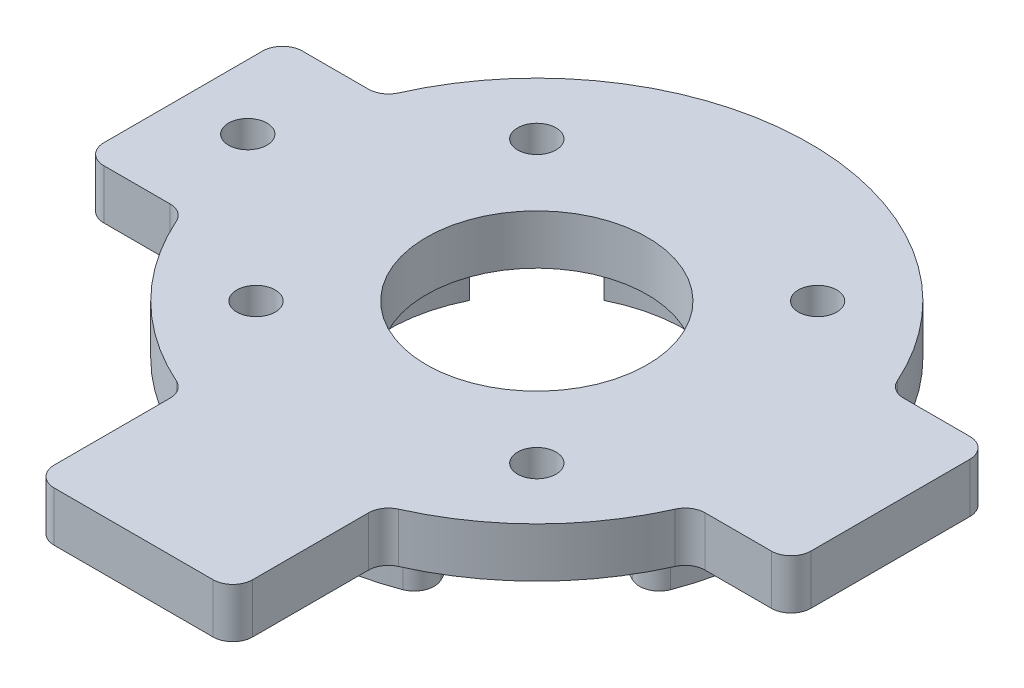
SolidWorks part; units mm, degrees
ref_plane "Front" through (0, 0, 0) normal (0, 0, 1) x (1, 0, 0)
ref_plane "Top" through (0, 0, 0) normal (0, 1, 0) x (1, 0, 0)
ref_plane "Right" through (0, 0, 0) normal (1, 0, 0) x (0, 0, -1)
sketch "Sketch1" plane through (0, 0, 0) normal (0, 1, 0) x (1, 0, 0)
  line L0 (0, -34.925) -> (0, 34.925) construction
  line L1 (-17.9605, 17.9605) -> (17.9605, 17.9605) construction
  line L2 (-17.9605, 17.9605) -> (-17.9605, -17.9605) construction
  line L3 (-17.9605, -17.9605) -> (17.9605, -17.9605) construction
  line L4 (17.9605, 17.9605) -> (17.9605, -17.9605) construction
  line L5 (-17.9605, 17.9605) -> (17.9605, -17.9605) construction
  line L6 (-17.9605, -17.9605) -> (17.9605, 17.9605) construction
  line L7 (-19.05, 50.8) -> (19.05, 50.8) construction
  line L8 (-19.05, 50.8) -> (-19.05, -50.8) construction
  line L9 (-19.05, -50.8) -> (19.05, -50.8) construction
  line L10 (19.05, 50.8) -> (19.05, -50.8) construction
  line L11 (-19.05, 50.8) -> (19.05, -50.8) construction
  line L12 (-19.05, -50.8) -> (19.05, 50.8) construction
  line L13 (12.7, -51.5841) -> (-12.7, -51.5841)
  line L14 (12.7, -51.5841) -> (12.7, -32.5341)
  line L15 (12.7, -32.5341) -> (-12.7, -32.5341)
  line L16 (-12.7, -51.5841) -> (-12.7, -32.5341)
  line L17 (-45.2341, 0) -> (0, 0) construction
  line L18 (-32.5341, 12.7) -> (-45.2341, 12.7)
  line L19 (-32.5341, 12.7) -> (-32.5341, -12.7)
  line L20 (-32.5341, -12.7) -> (-45.2341, -12.7)
  line L21 (-45.2341, 12.7) -> (-45.2341, -12.7)
  line L22 (32.5341, -12.7) -> (45.2341, -12.7)
  line L23 (45.2341, 12.7) -> (45.2341, -12.7)
  line L24 (32.5341, 12.7) -> (45.2341, 12.7)
  circle A0 centre (0, 0) radius 25.4 construction
  circle A1 centre (0, 0) radius 34.925
  circle A2 centre (0, 0) radius 14.1288
  point P0 (0, 0)
  point P18 (0, -32.5341)
  dimension "D1" = 50.8
  dimension "D4" = 69.85
  dimension "D5" = 28.2575
  dimension "D2" = 101.6
  dimension "D3" = 38.1
  dimension "D6" = 19.05
  dimension "D7" = 25.4
  dimension "D8" = 25.4
  dimension "D9" = 12.7
extrude "Stock Extrude" add sketch "Sketch1" along normal blind 6.35 contours A1 L18 L21 L20 | L15 A1 L19 A2 | A1 L22 L23 L24 | L19 A1 | A1 L16 L13 L14 | L15 A1
hole_wizard "#10 (0.1935) Diameter Hole1" positions "Sketch2" profile "Sketch3" hole size "#10" standard "ANSI Inch" end condition through all
sketch "Sketch2" plane through (0, 6.35, 0) normal (0, 1, 0) x (1, 0, 0)
  point P0 (-17.9605, 17.9605)
  point P3 (17.9605, 17.9605)
  point P6 (-17.9605, -17.9605)
  point P9 (17.9605, -17.9605)
sketch "Sketch3" plane through (-17.9605, 6.35, -17.9605) normal (1, 0, 0) x (0, 0, 1)
  line L0 (0, 0) -> (0, 6.35)
  line L1 (0, 6.35) -> (2.4574, 6.35)
  line L2 (2.4574, 6.35) -> (2.4574, 0)
  line L5 (2.4574, 0) -> (0, 0)
  line L11 (0, -6.35) -> (0, 107.95) construction
  dimension "Thru Hole Dia." = 4.9149
  dimension "Thru Hole Depth" = 6.35
sketch "Sketch4" plane through (0, 0, 0) normal (0, -1, 0) x (1, 0, 0)
  line L6 (-26.7352, -13.2648) -> (26.7352, 13.2648)
  line L7 (13.2648, -26.7352) -> (-13.2648, 26.7352)
  line L8 (-17.9605, -17.9605) -> (17.9605, 17.9605) construction
  line L9 (-17.9605, 17.9605) -> (17.9605, -17.9605) construction
  line L10 (-17.9605, -17.9605) -> (17.9605, 17.9605) construction
  line L11 (-17.9605, 17.9605) -> (17.9605, -17.9605) construction
  line L12 (26.7352, -13.2648) -> (-26.7352, 13.2648)
  line L13 (-13.2648, -26.7352) -> (13.2648, 26.7352)
  circle A1 centre (0, 0) radius 25.4 construction
  circle A2 centre (0, 0) radius 25.4 construction
  circle A3 centre (0, 0) radius 29.845
  circle A4 centre (0, 0) radius 19.05
  point P9 (0, 0)
  point P13 (0, 0)
  dimension "D5" = 38.1
  dimension "D1" = 38.1
  dimension "D3" = 19.05
  dimension "D4" = 19.05
  dimension "D2" = 4.445
extrude "Boss-Extrude2" add sketch "Sketch4" along normal blind 6.35 contours A4 L12 A3 L6 | A4 L13 A3 L7 | A4 L12 A3 L6 | A4 L13 A3 L7
fillet "Fillet2" radius 2.54 8 edges at (-26.7352, -3.175, -13.2648) (-26.7352, -3.175, 13.2648) (-13.2648, -3.175, 26.7352) (13.2648, -3.175, 26.7352) (26.7352, -3.175, 13.2648) (26.7352, -3.175, -13.2648) (-13.2648, -3.175, -26.7352) (13.2648, -3.175, -26.7352)
fillet "Fillet3" radius 0.254 20 edges at (10.2751, 0, -20.7094) (12.1747, 0, -26.4045) (0, 0, -29.845) (-12.1747, 0, -26.4045) (-20.7094, 0, -10.2751) (-26.4045, 0, -12.1747) (-29.845, 0, 0) (-20.7094, 0, 10.2751) (10.2751, 0, 20.7094) (12.1747, 0, 26.4045) (-10.2751, 0, 20.7094) (-12.1747, 0, 26.4045) (20.7094, 0, -10.2751) (26.4045, 0, -12.1747) (20.7094, 0, 10.2751) (26.4045, 0, 12.1747) (-10.2751, 0, -20.7094) (-26.4045, 0, 12.1747) (0, 0, 29.845) (29.845, 0, 0)
fillet "Fillet4" radius 2.54 12 edges at (-45.2341, 3.175, 12.7) (-45.2341, 3.175, -12.7) (-32.5341, 3.175, -12.7) (32.5341, 3.175, -12.7) (45.2341, 3.175, -12.7) (45.2341, 3.175, 12.7) (12.7, 3.175, 32.5341) (12.7, 3.175, 51.5841) (-12.7, 3.175, 51.5841) (-12.7, 3.175, 32.5341) (-32.5341, 3.175, 12.7) (32.5341, 3.175, 12.7)
hole_wizard "#10 (0.1935) Diameter Hole2" positions "Sketch5" profile "Sketch6" hole size "#10" standard "ANSI Inch" end condition through all
sketch "Sketch5" plane through (0, 6.35, 0) normal (0, 1, 0) x (1, 0, 0)
  line L0 (-45.2341, 0) -> (-36.9791, 0) construction
  line L1 (-45.2341, 10.16) -> (-45.2341, -10.16) construction
  point P0 (-36.9791, 0)
  point P9 (-37.084, 0)
  dimension "D1" = 8.255
sketch "Sketch6" plane through (-36.9791, 6.35, 0) normal (1, 0, 0) x (0, 0, 1)
  line L0 (0, 0) -> (0, 12.7)
  line L1 (0, 12.7) -> (2.4574, 12.7)
  line L2 (2.4574, 12.7) -> (2.4574, 0)
  line L5 (2.4574, 0) -> (0, 0)
  line L11 (0, -6.35) -> (0, 107.95) construction
  dimension "Thru Hole Dia." = 4.9149
  dimension "Thru Hole Depth" = 12.7
equation "\"D4@Sketch4\"=\"D3@Sketch4\""
